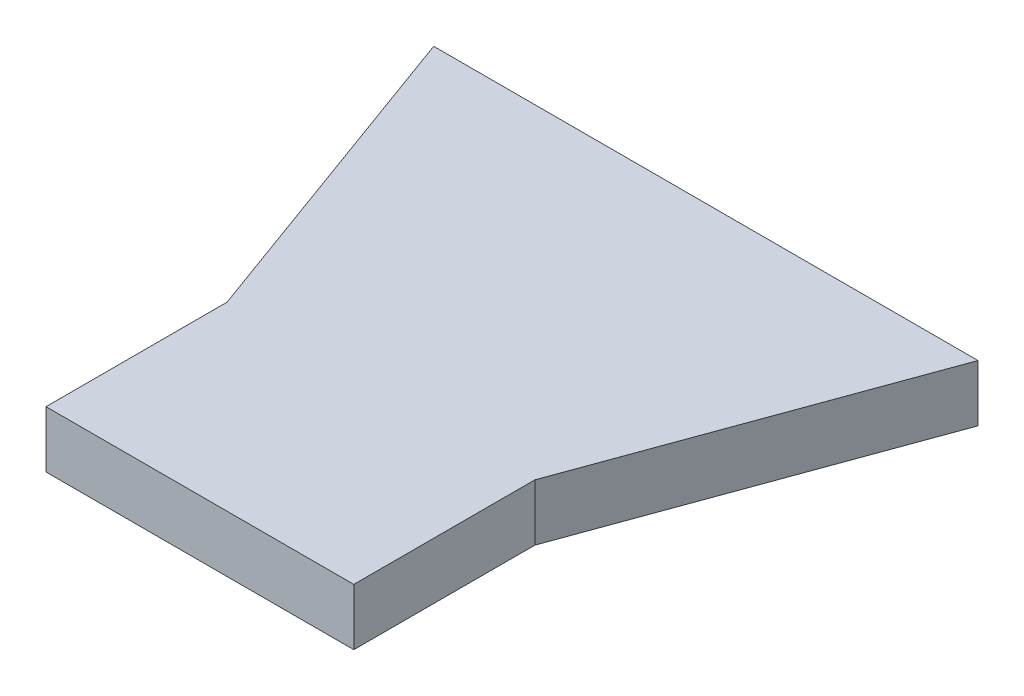
SolidWorks part; units mm, degrees
ref_plane "Front Plane" through (0, 0, 0) normal (0, 0, 1) x (1, 0, 0)
ref_plane "Top Plane" through (0, 0, 0) normal (0, 1, 0) x (1, 0, 0)
ref_plane "Right Plane" through (0, 0, 0) normal (1, 0, 0) x (0, 0, -1)
sketch "Sketch2" plane through (0, 0, 0) normal (0, 1, 0) x (1, 0, 0)
  line L1 (0, 0) -> (136, 0)
  line L2 (0, 0) -> (0, 80)
  line L4 (136, 0) -> (136, 80)
  line L9 (0, 80) -> (-52.2535, 223.5654)
  line L10 (-52.2535, 223.5654) -> (188.2535, 223.5654)
  line L11 (188.2535, 223.5654) -> (136, 80)
  line L12 (68, 0) -> (68, 237.9567) construction
  point P7 (68, 223.5654)
  point P21 (136, 81.0355)
  dimension "D1" = 136
  dimension "D2" = 160
  dimension "D4" = 80
extrude "Boss-Extrude1" add sketch "Sketch2" along normal blind 25
shell "Shell1" [suppressed] thickness 5
sketch "Sketch3" [suppressed] plane through (0, 0, 0) normal (-1, 0, 0) x (0, 0, 1)
  circle A0 centre (95.5727, 43.484) radius 105
  dimension "D1" = 210
sketch "Sketch24" [suppressed] plane through (0, 25, 0) normal (0, 1, 0) x (1, 0, 0)
  line L0 (131, 80.8816) -> (136, 80)
  line L1 (136, 0) -> (136, 80) construction
  line L2 (136, 80) -> (188.2535, 223.5654) construction
  line L3 (136, 80) -> (136, 70.5243)
  line L4 (136, 70.5243) -> (131, 70.5243)
  line L5 (131, 0) -> (131, 80.8816) construction
  line L6 (131, 70.5243) -> (131, 80.8816)
extrude "Cut-Extrude3" [suppressed] cut sketch "Sketch24" against normal up to surface (20 mm away)
ref_plane "Plane1" through (68, 0, 0) normal (-1, 0, 0) x (0, 0, 1)
mirror "Mirror1" [suppressed] about plane through (68, 0, 0) normal (-1, 0, 0)
sketch "Sketch4" [suppressed] plane through (131, 0, 0) normal (-1, 0, 0) x (0, 0, 1)
  line L0 (0, 40) -> (0, 0) construction
  line L1 (0, 35) -> (-80, 35)
  line L2 (0, 35) -> (0, 40)
  line L3 (0, 40) -> (-80, 40)
  line L4 (-80, 35) -> (-80, 40)
  dimension "D1" = 5
extrude "Boss-Extrude2" [suppressed] add sketch "Sketch4" along normal up to surface (126 mm away)
sketch "Sketch5" plane through (0, 40, 0) normal (0, 1, 0) x (1, 0, 0)
  line L0 (0, 0) -> (5, 0) construction
  line L3 (17, 0) -> (0, 0) construction
  line L4 (119, 0) -> (136, 0) construction
  circle A0 centre (119, 0) radius 15.4177
  circle A1 centre (85, 0) radius 15.4177
  circle A2 centre (51, 0) radius 15.4177
  circle A3 centre (17, 0) radius 15.4177
  dimension "D1" = 4
extrude "Cut-Extrude2" [suppressed] cut sketch "Sketch5" against normal up to surface and the other way through all
sketch "Sketch6" plane through (0, 0, 0) normal (-1, 0, 0) x (0, 0, 1)
  line L0 (-80, 40) -> (-247.5483, 130.1828)
sketch "Sketch7" [suppressed] plane through (0, 0, -80) normal (0, 0, -1) x (-1, 0, 0)
  line L0 (-5, 35) -> (-131, 35) construction
  line L1 (-136, 40) -> (0, 40)
  line L2 (-136, 40) -> (-136, 35)
  line L3 (-136, 35) -> (0, 35)
  line L4 (0, 40) -> (0, 35)
sweep "Sweep1" [suppressed] add profiles "Sketch7" path "Sketch6"
fillet "Fillet1" [suppressed] radius 45
sketch "Bend-Lines11" plane through (0, 0, 0) normal (0, 1, 0) x (1, 0, 0)
sketch "Bounding-Box11" plane through (0, 0, 0) normal (0, 1, 0) x (1, 0, 0)
